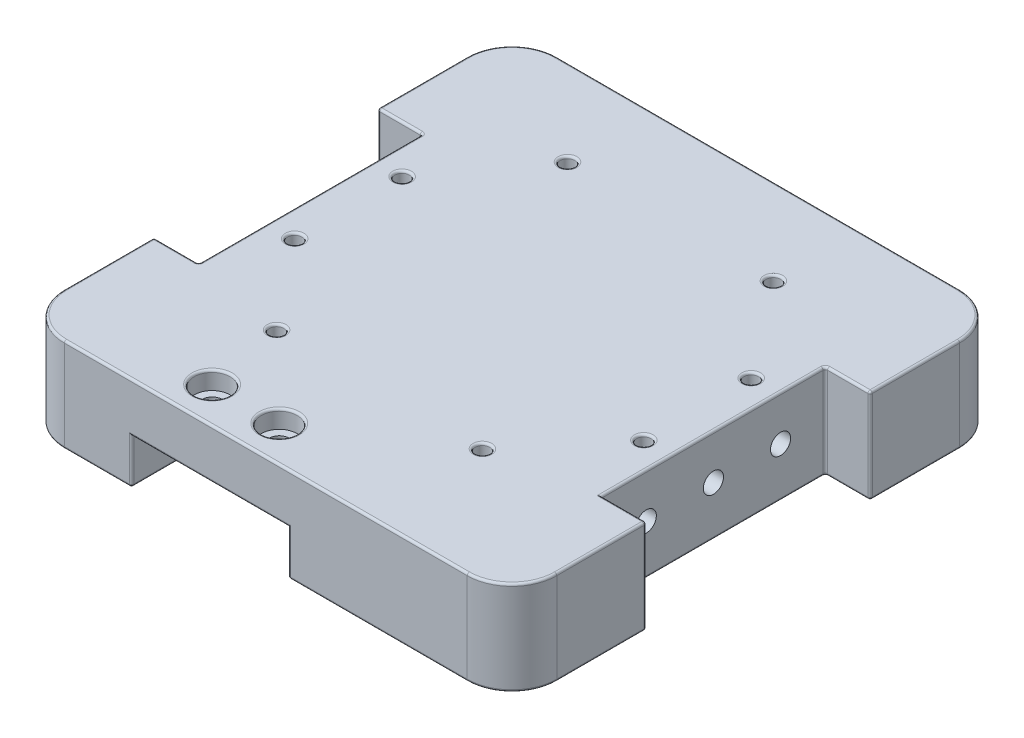
SolidWorks part; units mm, degrees
ref_plane "Front Plane" through (0, 0, 0) normal (0, 0, 1) x (1, 0, 0)
ref_plane "Top Plane" through (0, 0, 0) normal (0, 1, 0) x (1, 0, 0)
ref_plane "Right Plane" through (0, 0, 0) normal (1, 0, 0) x (0, 0, -1)
sketch "Sketch2" plane through (0, 0, 0) normal (0, 1, 0) x (1, 0, 0)
  line L1 (0, 110) -> (110, 110)
  line L2 (0, 110) -> (0, 0)
  line L3 (0, 0) -> (110, 0)
  line L4 (110, 110) -> (110, 0)
  dimension "D1" = 110
  dimension "D2" = 110
extrude "Boss-Extrude2" add sketch "Sketch2" along normal blind 21
fillet "Fillet1" radius 10 4 edges at (110, 10.5, -110) (110, 10.5, 0) (0, 10.5, -110) (0, 10.5, 0)
sketch "Sketch13" plane through (0, 21, 0) normal (0, 1, 0) x (1, 0, 0)
  line L0 (0, 100) -> (0, 10) construction
  line L1 (0, 80) -> (10, 80)
  line L2 (0, 80) -> (0, 30)
  line L3 (0, 30) -> (10, 30)
  line L4 (10, 80) -> (10, 30)
  line L5 (110, 10) -> (110, 100) construction
  line L6 (110, 80) -> (100, 80)
  line L7 (110, 80) -> (110, 30)
  line L8 (110, 30) -> (100, 30)
  line L9 (100, 80) -> (100, 30)
  line L10 (100, 110) -> (10, 110) construction
  dimension "D1" = 10
  dimension "D2" = 10
  dimension "D3" = 30
  dimension "D4" = 50
extrude "Cut-Extrude10" cut sketch "Sketch13" against normal blind 30
sketch "Sketch20" plane through (0, 0, 0) normal (0, -1, 0) x (1, 0, 0)
  line L0 (10, 0) -> (100, 0) construction
  line L1 (25, 0) -> (60, 0)
  line L2 (25, 0) -> (25, -20)
  line L3 (25, -20) -> (60, -20)
  line L4 (60, 0) -> (60, -20)
  line L7 (0, -30) -> (0, -10) construction
  dimension "D1" = 35
  dimension "D2" = 20
  dimension "D3" = 25
extrude "Cut-Extrude12" cut sketch "Sketch20" against normal blind 10
sketch "Sketch21" plane through (0, 10, 0) normal (0, -1, 0) x (-1, 0, 0)
  line L0 (-60, 0) -> (-25, 0) construction
  line L1 (-35, 8) -> (-25, 8) construction
  line L2 (-25, 0) -> (-25, 20) construction
  line L3 (-50, 8) -> (-60, 8) construction
  line L4 (-60, 20) -> (-60, 0) construction
  circle A0 centre (-50, 8) radius 2.25
  circle A1 centre (-35, 8) radius 2.25
  dimension "D3" = 4.5
  dimension "D1" = 15
  dimension "D2" = 8
extrude "Cut-Extrude13" cut sketch "Sketch21" against normal blind 15
sketch "Sketch47" plane through (0, 21, 0) normal (0, 1, 0) x (1, 0, 0)
  circle A0 centre (50, 8) radius 4
  circle A1 centre (35, 8) radius 4
  dimension "D1" = 8
extrude "Cut-Extrude24" cut sketch "Sketch47" against normal blind 4
sketch "Sketch14" plane through (100, 0, 0) normal (1, 0, 0) x (0, 0, -1)
  line L0 (80, 0) -> (80, 21) construction
  line L2 (80, 0) -> (30, 0) construction
  circle A0 centre (40, 11) radius 2.25
  circle A1 centre (70, 11) radius 2.25
  circle A2 centre (55, 11) radius 2.25
  dimension "D5" = 4.5
  dimension "D1" = 15
  dimension "D2" = 10
  dimension "D3" = 11
  dimension "D6" = 15
extrude "Cut-Extrude11" cut sketch "Sketch14" against normal up to vertex
sketch "草图1" plane through (0, 21, 0) normal (0, 1, 0) x (1, 0, 0)
  line L0 (0, 100) -> (0, 80) construction
  line L3 (100, 110) -> (10, 110) construction
  circle A0 centre (94, 69.4489) radius 1.6 construction
  circle A1 centre (94, 45.4489) radius 1.6 construction
  circle A2 centre (94, 69.4489) radius 1.6
  circle A3 centre (94, 45.4489) radius 1.6
  circle A4 centre (16, 69.4489) radius 1.6 construction
  circle A5 centre (16, 45.4489) radius 1.6 construction
  circle A6 centre (16, 69.4489) radius 1.6
  circle A7 centre (16, 45.4489) radius 1.6
  circle A8 centre (77.65, 90.75) radius 1.6
  circle A9 centre (31.65, 90.75) radius 1.6
  circle A10 centre (77.65, 25.75) radius 1.6
  circle A11 centre (31.65, 25.75) radius 1.6
  dimension "D1" = 3.2
  dimension "D2" = 46
  dimension "D3" = 31.65
  dimension "D4" = 19.25
  dimension "D5" = 65
extrude "切除-拉伸1" cut sketch "草图1" against normal through all and the other way through all
fillet "圆角1" radius 0.5 64 edges at (0, 0, -20) (0, 21, -20) (107.0711, 21, -2.9289) (107.0711, 0, -2.9289) (110, 21, -90) (107.0711, 21, -107.0711) (55, 21, -110) (2.9289, 21, -107.0711) (110, 0, -90) (107.0711, 0, -107.0711) (55, 0, -110) (2.9289, 0, -107.0711) (55, 21, 0) (80, 0, 0) (60, 5, 0) (42.5, 10, 0) (25, 5, 0) (17.5, 0, 0) (2.9289, 0, -2.9289) (2.9289, 21, -2.9289) (110, 21, -20) (110, 10.5, -30) (110, 0, -20) (0, 21, -90) (0, 10.5, -80) (0, 0, -90) (5, 21, -80) (105, 0, -30) (105, 0, -80) (105, 21, -80) (100, 21, -55) (105, 21, -30) (10, 10.5, -80) (10, 21, -55) (5, 21, -30) (5, 0, -30) (10, 0, -55) (5, 0, -80) (100, 0, -55) (100, 10.5, -80) (110, 10.5, -80) (10, 10.5, -30) (0, 10.5, -30) (60, 0, -10) (25, 0, -10) (42.5, 0, -20) (31.65, 0, -24.15) (94, 0, -67.8489) (77.65, 0, -24.15) (31.65, 0, -92.35) (94, 0, -43.8489) (16, 0, -67.8489) (16, 0, -43.8489) (77.65, 0, -89.15) (35, 21, -4) (50, 21, -4) (94, 21, -67.8489) (77.65, 21, -24.15) (31.65, 21, -24.15) (31.65, 21, -89.15) (94, 21, -43.8489) (16, 21, -67.8489) (16, 21, -43.8489) (77.65, 21, -89.15)
